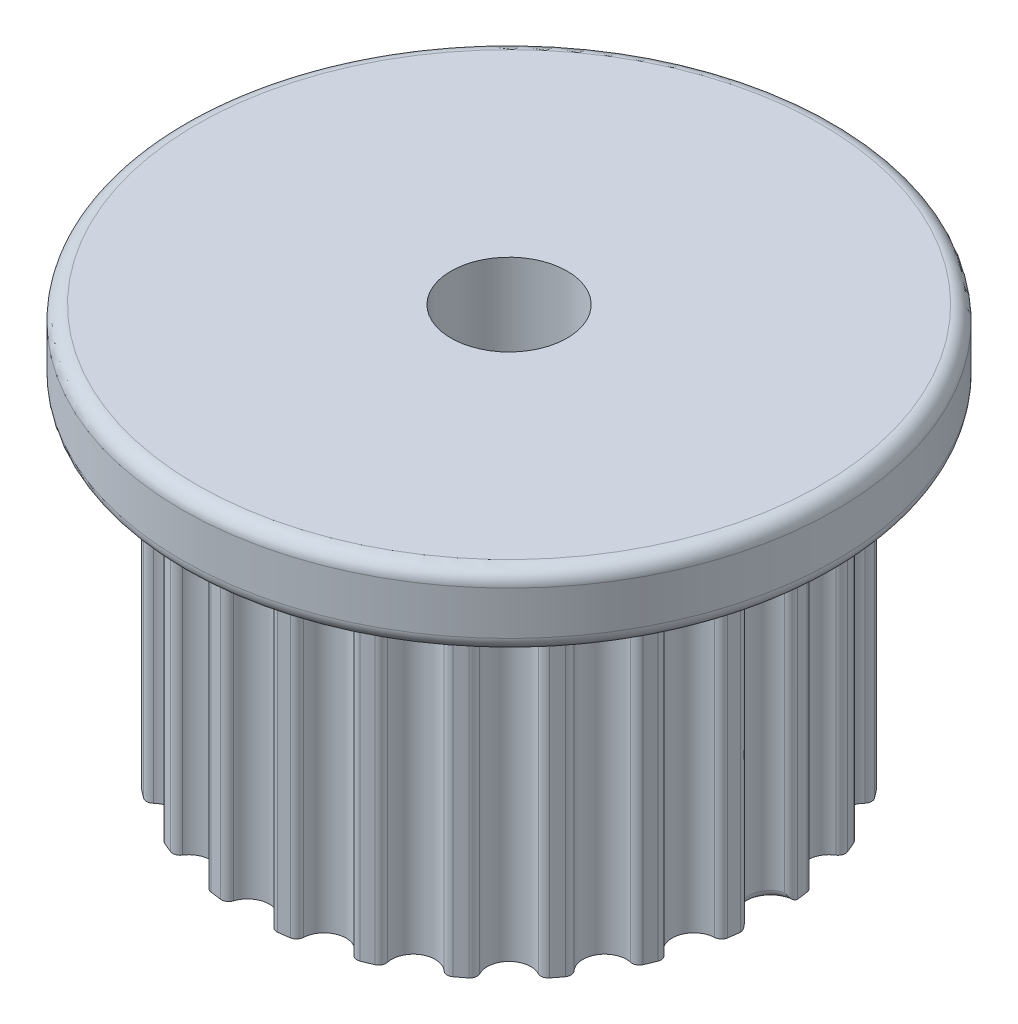
SolidWorks part; units mm, degrees
ref_plane "Plano frontal" through (0, 0, 0) normal (0, 0, 1) x (1, 0, 0)
ref_plane "Plano superior" through (0, 0, 0) normal (0, 1, 0) x (1, 0, 0)
ref_plane "Plano direito" through (0, 0, 0) normal (1, 0, 0) x (0, 0, -1)
sketch "Esboço1" plane through (0, 0, 0) normal (0, 1, 0) x (1, 0, 0)
  circle A0 centre (0, 0) radius 4.5
  dimension "D1" = 9
extrude "Ressalto-extrusão1" add sketch "Esboço1" along normal blind 1
sketch "Esboço4" plane through (0, 0, 0) normal (0, -1, 0) x (1, 0, 0)
  circle A0 centre (0, 0) radius 0.8
  circle A1 centre (0, 0) radius 3.6
  dimension "D1" = 1.6
  dimension "D2" = 7.2
extrude "Ressalto-extrusão3" add sketch "Esboço4" along normal blind 4.5
sketch "Esboço5" plane through (0, -4.5, 0) normal (0, -1, 0) x (1, 0, 0)
  circle A0 centre (0, 3.6) radius 0.3
  circle A1 centre (0, 0) radius 3.6 construction
  circle A2 centre (0, 0) radius 3.6 construction
  circle A3 centre (0.9317, 3.4773) radius 0.3
  circle A4 centre (1.8, 3.1177) radius 0.3
  circle A5 centre (2.5456, 2.5456) radius 0.3
  circle A6 centre (3.1177, 1.8) radius 0.3
  circle A7 centre (3.4773, 0.9317) radius 0.3
  circle A8 centre (3.6, 0) radius 0.3
  circle A9 centre (3.4773, -0.9317) radius 0.3
  circle A10 centre (3.1177, -1.8) radius 0.3
  circle A11 centre (2.5456, -2.5456) radius 0.3
  circle A12 centre (1.8, -3.1177) radius 0.3
  circle A13 centre (0.9317, -3.4773) radius 0.3
  circle A14 centre (0, -3.6) radius 0.3
  circle A15 centre (-0.9317, -3.4773) radius 0.3
  circle A16 centre (-1.8, -3.1177) radius 0.3
  circle A17 centre (-2.5456, -2.5456) radius 0.3
  circle A18 centre (-3.1177, -1.8) radius 0.3
  circle A19 centre (-3.4773, -0.9317) radius 0.3
  circle A20 centre (-3.6, 0) radius 0.3
  circle A21 centre (-3.4773, 0.9317) radius 0.3
  circle A22 centre (-3.1177, 1.8) radius 0.3
  circle A23 centre (-2.5456, 2.5456) radius 0.3
  circle A24 centre (-1.8, 3.1177) radius 0.3
  circle A25 centre (-0.9317, 3.4773) radius 0.3
  point P55 (0, 0)
  dimension "D1" = 0.6
  dimension "D2" = 24
extrude "Corte-extrusão2" cut sketch "Esboço5" against normal up to surface (4.5 mm away) up to face at (0, 0, 3.6)
fillet "Filete2" radius 0.1 97 edges at (-3.3, 0, 0) (-3.5692, 0, -0.4699) (-3.5692, 0, 0.4699) (-3.1876, 0, -0.8541) (-3.1876, 0, 0.8541) (-3.326, 0, -1.3777) (-3.326, 0, 1.3777) (-2.8579, 0, -1.65) (-2.8579, 0, 1.65) (-2.8561, 0, -2.1915) (-2.8561, 0, 2.1915) (-2.3335, 0, -2.3335) (-2.3335, 0, 2.3335) (-2.1915, 0, -2.8561) (-2.1915, 0, 2.8561) (-1.65, 0, -2.8579) (-1.65, 0, 2.8579) (-1.3777, 0, -3.326) (-1.3777, 0, 3.326) (-0.8541, 0, -3.1876) (-0.8541, 0, 3.1876) (-0.4699, 0, -3.5692) (-0.4699, 0, 3.5692) (0, 0, -3.3) (0, 0, 3.3) (0.4699, 0, -3.5692) (0.4699, 0, 3.5692) (0.8541, 0, -3.1876) (0.8541, 0, 3.1876) (1.3777, 0, -3.326) (1.3777, 0, 3.326) (1.65, 0, -2.8579) (1.65, 0, 2.8579) (2.1915, 0, -2.8561) (2.1915, 0, 2.8561) (2.3335, 0, -2.3335) (2.3335, 0, 2.3335) (2.8561, 0, -2.1915) (2.8561, 0, 2.1915) (2.8579, 0, -1.65) (2.8579, 0, 1.65) (3.326, 0, -1.3777) (3.326, 0, 1.3777) (3.1876, 0, -0.8541) (3.1876, 0, 0.8541) (3.5692, 0, -0.4699) (3.5692, 0, 0.4699) (3.5875, -2.25, 0.2997) (3.5875, -2.25, -0.2997) (3.3, -4.5, 0) (3.3, 0, 0) (-2.7487, -2.25, 2.3248) (-2.3248, -2.25, 2.7487) (-3.2567, -2.25, 1.5342) (-2.957, -2.25, 2.0533) (-3.5428, -2.25, 0.639) (-3.3877, -2.25, 1.218) (-3.5875, -2.25, -0.2997) (-3.5875, -2.25, 0.2997) (-3.3877, -2.25, -1.218) (-3.5428, -2.25, -0.639) (-2.957, -2.25, -2.0533) (-3.2567, -2.25, -1.5342) (-2.3248, -2.25, -2.7487) (-2.7487, -2.25, -2.3248) (-1.5342, -2.25, -3.2567) (-2.0533, -2.25, -2.957) (-0.639, -2.25, -3.5428) (-1.218, -2.25, -3.3877) (0.2997, -2.25, -3.5875) (-0.2997, -2.25, -3.5875) (1.218, -2.25, -3.3877) (0.639, -2.25, -3.5428) (2.0533, -2.25, -2.957) (1.5342, -2.25, -3.2567) (2.7487, -2.25, -2.3248) (2.3248, -2.25, -2.7487) (3.2567, -2.25, -1.5342) (2.957, -2.25, -2.0533) (3.5428, -2.25, -0.639) (3.3877, -2.25, -1.218) (3.3877, -2.25, 1.218) (3.5428, -2.25, 0.639) (2.957, -2.25, 2.0533) (3.2567, -2.25, 1.5342) (2.3248, -2.25, 2.7487) (2.7487, -2.25, 2.3248) (1.5342, -2.25, 3.2567) (2.0533, -2.25, 2.957) (0.639, -2.25, 3.5428) (1.218, -2.25, 3.3877) (-0.2997, -2.25, 3.5875) (0.2997, -2.25, 3.5875) (-1.218, -2.25, 3.3877) (-0.639, -2.25, 3.5428) (-2.0533, -2.25, 2.957) (-1.5342, -2.25, 3.2567)
sketch "Esboço6" plane through (0, 0, 0) normal (0, -1, 0) x (1, 0, 0)
  circle A0 centre (0, 0) radius 0.8
  dimension "D1" = 1.6
extrude "Corte-extrusão3" cut sketch "Esboço6" against normal through all
fillet "Filete3" radius 0.2 2 edges at (0, 0, 4.5) (0, 1, 4.5)
